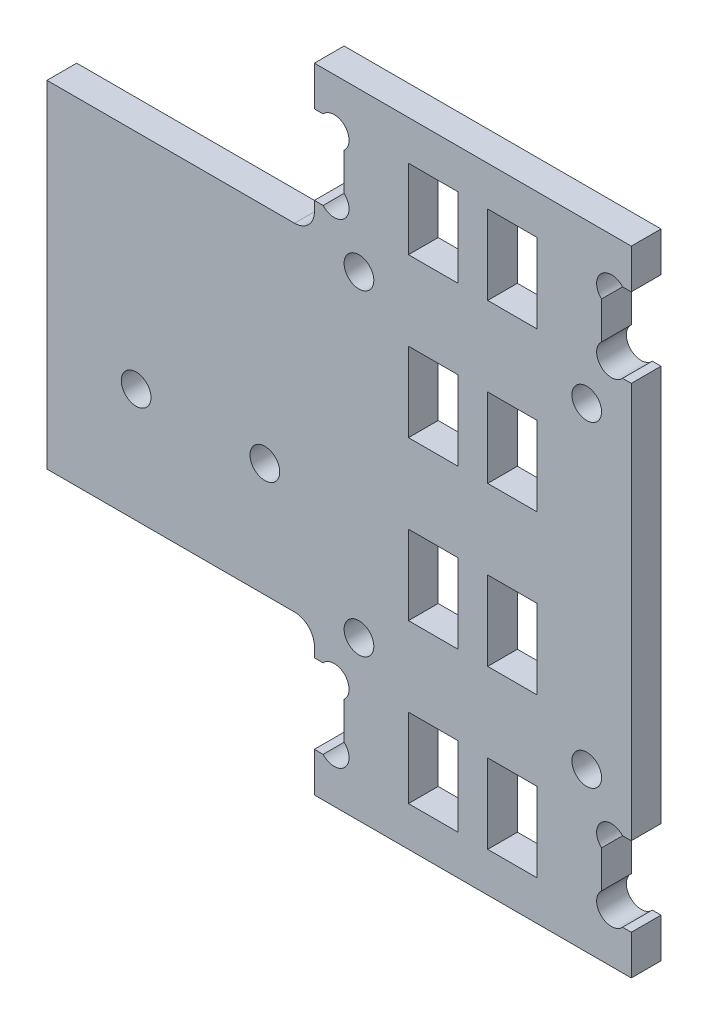
SolidWorks part; units mm, degrees
material "Thornel Mat VMA"
ref_plane "前视基准面" through (0, 0, 0) normal (0, 0, 1) x (1, 0, 0)
ref_plane "上视基准面" through (0, 0, 0) normal (0, 1, 0) x (1, 0, 0)
ref_plane "右视基准面" through (0, 0, 0) normal (1, 0, 0) x (0, 0, -1)
sketch "草图1" plane through (0, 0, 0) normal (0, 0, 1) x (1, 0, 0)
  line L1 (-16, -32) -> (16, -32)
  line L2 (-16, -32) -> (-16, 32)
  line L3 (-16, 32) -> (16, 32)
  line L4 (16, -32) -> (16, 32)
  line L5 (-16, -32) -> (16, 32) construction
  line L6 (-16, 32) -> (16, -32) construction
  point P0 (0, 0)
  dimension "D1" = 32
  dimension "D2" = 64
extrude "凸台-拉伸1" add sketch "草图1" along normal blind 3
sketch "草图2" plane through (0, 0, 3) normal (0, 0, 1) x (1, 0, 0)
  line L1 (-4, -8) -> (4, -8)
  line L2 (-4, -8) -> (-4, 8)
  line L3 (-4, 8) -> (4, 8)
  line L4 (4, -8) -> (4, 8)
  line L5 (-4, -8) -> (4, 8) construction
  line L6 (-4, 8) -> (4, -8) construction
  line L7 (1.5, 4) -> (6.5, 4)
  line L8 (1.5, 4) -> (1.5, 12)
  line L9 (1.5, 12) -> (6.5, 12)
  line L10 (6.5, 4) -> (6.5, 12)
  line L11 (1.5, 4) -> (6.5, 12) construction
  line L12 (1.5, 12) -> (6.5, 4) construction
  point P0 (0, 0)
  dimension "D1" = 5
  dimension "D2" = 8
  dimension "D3" = 8
  dimension "D4" = 16
extrude "切除-拉伸1" cut sketch "草图2" against normal through all contours L7 L10 L9 L8 L3 L4 | L8 L7 L4 L3
mirror "镜向1" about plane through (0, 0, 0) normal (1, 0, 0) of "切除-拉伸1"
mirror "镜向2" about plane through (0, 0, 0) normal (0, 1, 0) of "镜向1", "切除-拉伸1"
sketch "草图4" plane through (0, 0, 3) normal (0, 0, 1) x (1, 0, 0)
  line L0 (16, -32) -> (16, 32) construction
  line L1 (16, 4) -> (13, 4)
  line L2 (16, 4) -> (16, 12)
  line L3 (16, 12) -> (13, 12)
  line L4 (13, 4) -> (13, 12)
  dimension "D1" = 4
  dimension "D2" = 3
  dimension "D3" = 8
extrude "切除-拉伸3" cut sketch "草图4" against normal through all
mirror "镜向5" about plane through (0, 0, 0) normal (1, 0, 0) of "切除-拉伸3"
mirror "镜向6" about plane through (0, 0, 0) normal (0, 1, 0) of "镜向5", "切除-拉伸3"
sketch "草图6" plane through (0, 0, 3) normal (0, 0, 1) x (1, 0, 0)
  line L0 (16, 12) -> (16, 32) construction
  line L1 (16, 20) -> (13, 20)
  line L2 (16, 20) -> (16, 28)
  line L3 (16, 28) -> (13, 28)
  line L4 (13, 20) -> (13, 28)
  dimension "D1" = 20
  dimension "D2" = 3
  dimension "D3" = 8
extrude "切除-拉伸4" cut sketch "草图6" against normal through all
mirror "镜向7" about plane through (0, 0, 0) normal (1, 0, 0) of "切除-拉伸4"
mirror "镜向8" about plane through (0, 0, 0) normal (0, 1, 0) of "镜向7", "切除-拉伸4"
sketch "草图7" plane through (0, 0, 3) normal (0, 0, 1) x (1, 0, 0)
  line L0 (-16, 28) -> (-13, 28) construction
  line L1 (-13, 28) -> (-13, 20) construction
  line L2 (-13, 20) -> (-16, 20) construction
  circle A0 centre (-14, 27) radius 1.5
  circle A1 centre (-14, 21) radius 1.5
  dimension "D1" = 3
  dimension "D2" = 1
  dimension "D3" = 1
  dimension "D4" = 1
  dimension "D5" = 3
  dimension "D6" = 1
extrude "切除-拉伸5" cut sketch "草图7" against normal through all
mirror "镜向9" about plane through (0, 0, 0) normal (1, 0, 0) of "切除-拉伸5"
mirror "镜向10" about plane through (0, 0, 0) normal (0, 1, 0) of "镜向9", "切除-拉伸5"
sketch "草图8" plane through (0, 0, 3) normal (0, 0, 1) x (1, 0, 0)
  line L0 (-16, 12) -> (-13, 12) construction
  line L1 (-13, 12) -> (-13, 4) construction
  line L2 (-13, 4) -> (-16, 4) construction
  circle A0 centre (-14, 11) radius 1.5
  circle A1 centre (-14, 5) radius 1.5
  dimension "D1" = 3
  dimension "D2" = 1
  dimension "D3" = 1
  dimension "D4" = 1
  dimension "D5" = 3
  dimension "D6" = 1
extrude "切除-拉伸6" cut sketch "草图8" against normal through all
mirror "镜向11" about plane through (0, 0, 0) normal (1, 0, 0) of "切除-拉伸6"
mirror "镜向12" about plane through (0, 0, 0) normal (0, 1, 0) of "镜向11", "切除-拉伸6"
sketch "草图11" plane through (0, 0, 3) normal (0, 0, 1) x (1, 0, 0)
  circle A0 centre (11.5, 16) radius 1.5
  dimension "D1" = 11.5
  dimension "D2" = 3
  dimension "D3" = 16
extrude "切除-拉伸9" cut sketch "草图11" against normal through all
mirror "镜向15" about plane through (0, 0, 0) normal (1, 0, 0) of "切除-拉伸9"
mirror "镜向16" about plane through (0, 0, 0) normal (0, 1, 0) of "镜向15", "切除-拉伸9"
sketch "草图12" plane through (0, 0, 3) normal (0, 0, 1) x (1, 0, 0)
  line L0 (6.5, 4) -> (6.5, 12) construction
  line L1 (1.5, 28) -> (6.5, 28)
  line L2 (1.5, 28) -> (1.5, 20)
  line L3 (1.5, 20) -> (6.5, 20)
  line L4 (6.5, 28) -> (6.5, 20)
  line L5 (1.5, 28) -> (6.5, 20) construction
  line L6 (1.5, 20) -> (6.5, 28) construction
  point P0 (4, 24)
  dimension "D1" = 8
  dimension "D2" = 5
  dimension "D3" = 20
extrude "切除-拉伸10" cut sketch "草图12" against normal through all
mirror "镜向17" about plane through (0, 0, 0) normal (1, 0, 0) of "切除-拉伸10"
mirror "镜向18" about plane through (0, 0, 0) normal (0, 1, 0) of "镜向17", "切除-拉伸10"
sketch "草图13" plane through (0, 0, 3) normal (0, 0, 1) x (1, 0, 0)
  line L0 (-16, 20) -> (-16, 12) construction
  line L1 (-16, 13.4596) -> (-12.0453, 13.4596)
  line L2 (-16, 13.4596) -> (-16, 2.6113)
  line L3 (-16, 2.6113) -> (-12.0453, 2.6113)
  line L4 (-12.0453, 13.4596) -> (-12.0453, 2.6113)
  line L5 (16, -4) -> (16, 4) construction
  line L6 (16, 2.6113) -> (11.7726, 2.6113)
  line L7 (16, 2.6113) -> (16, 13.4596)
  line L8 (16, 13.4596) -> (11.7726, 13.4596)
  line L9 (11.7726, 2.6113) -> (11.7726, 13.4596)
  line L10 (-16, 4) -> (-16, -4) construction
  line L11 (16, -2.5476) -> (11.7726, -2.5476)
  line L12 (16, -2.5476) -> (16, -13.203)
  line L13 (16, -13.203) -> (11.7726, -13.203)
  line L14 (11.7726, -2.5476) -> (11.7726, -13.203)
  line L15 (-16, -2.5476) -> (-12.0453, -2.5476)
  line L16 (-16, -2.5476) -> (-16, -13.203)
  line L17 (-16, -13.203) -> (-12.0453, -13.203)
  line L18 (-12.0453, -2.5476) -> (-12.0453, -13.203)
extrude "凸台-拉伸2" add sketch "草图13" against normal up to surface (3 mm away) up to face at (-4, -24, 0)
sketch "草图14" plane through (0, 0, 0) normal (0, 0, -1) x (-1, 0, 0)
  line L0 (16, 20) -> (16, -20) construction
  line L1 (16, -17) -> (43, -17)
  line L2 (16, -17) -> (16, 17)
  line L3 (16, 17) -> (43, 17)
  line L4 (43, -17) -> (43, 17)
  point P6 (43, 0)
  dimension "D1" = 34
  dimension "D2" = 27
extrude "凸台-拉伸3" add sketch "草图14" against normal up to surface (3 mm away) up to face at (0, 0, 3)
sketch "草图15" plane through (0, 0, 0) normal (0, 0, -1) x (-1, 0, 0)
  line L0 (43, -5.5) -> (16.2999, -5.5) construction
  line L1 (43, -17) -> (43, 17) construction
  line L2 (16, -17) -> (43, -17) construction
  circle A0 centre (34, -5.5) radius 1.5
  circle A1 centre (21, -5.5) radius 1.5
  dimension "D1" = 13
  dimension "D4" = 3
  dimension "D2" = 9
  dimension "D3" = 11.5
extrude "切除-拉伸11" cut sketch "草图15" against normal through all
fillet "圆角1" radius 2 2 edges at (-16, -17, 1.5) (-16, 17, 1.5)
